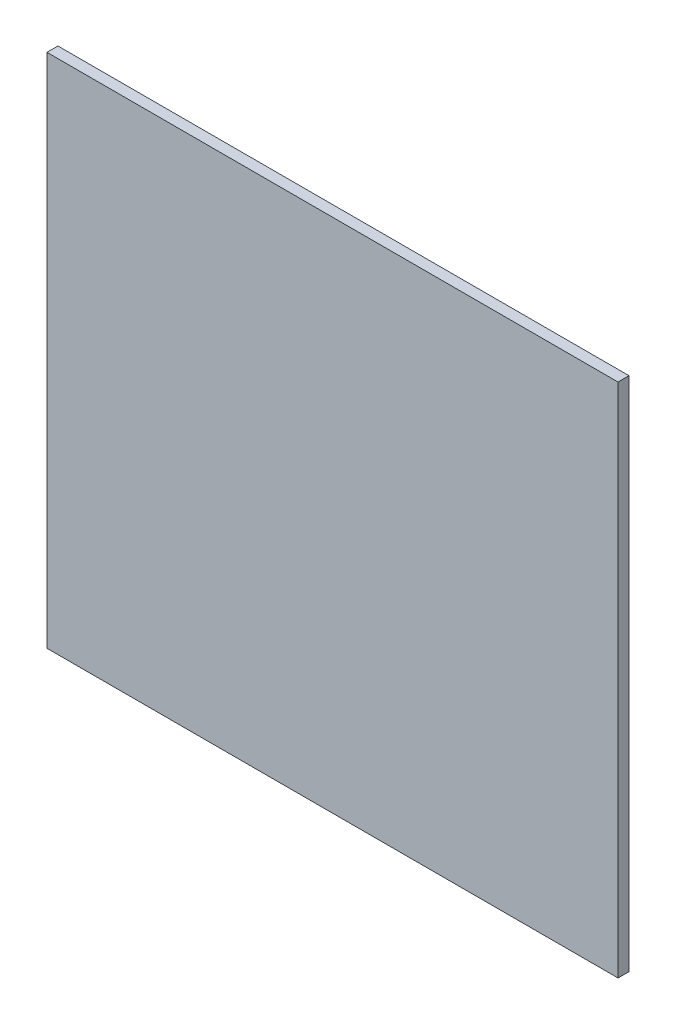
SolidWorks part; units mm, degrees
ref_plane "Front Plane" through (0, 0, 0) normal (0, 0, 1) x (1, 0, 0)
ref_plane "Top Plane" through (0, 0, 0) normal (0, 1, 0) x (1, 0, 0)
ref_plane "Right Plane" through (0, 0, 0) normal (1, 0, 0) x (0, 0, -1)
sketch "Esquisse1" plane through (0, 0, 0) normal (0, 0, 1) x (1, 0, 0)
  line L1 (0, 0) -> (-260, 0)
  line L2 (0, 0) -> (0, -235)
  line L3 (0, -235) -> (-260, -235)
  line L4 (-260, 0) -> (-260, -235)
  line L5 (-130, -235) -> (-130, 0) construction
  line L6 (0, -117.5) -> (-260, -117.5) construction
  point P140 (-130, -117.5)
  dimension "D1" = 260
  dimension "D2" = 235
extrude "Boss.-Extru.1" add sketch "Esquisse1" along normal blind 5
